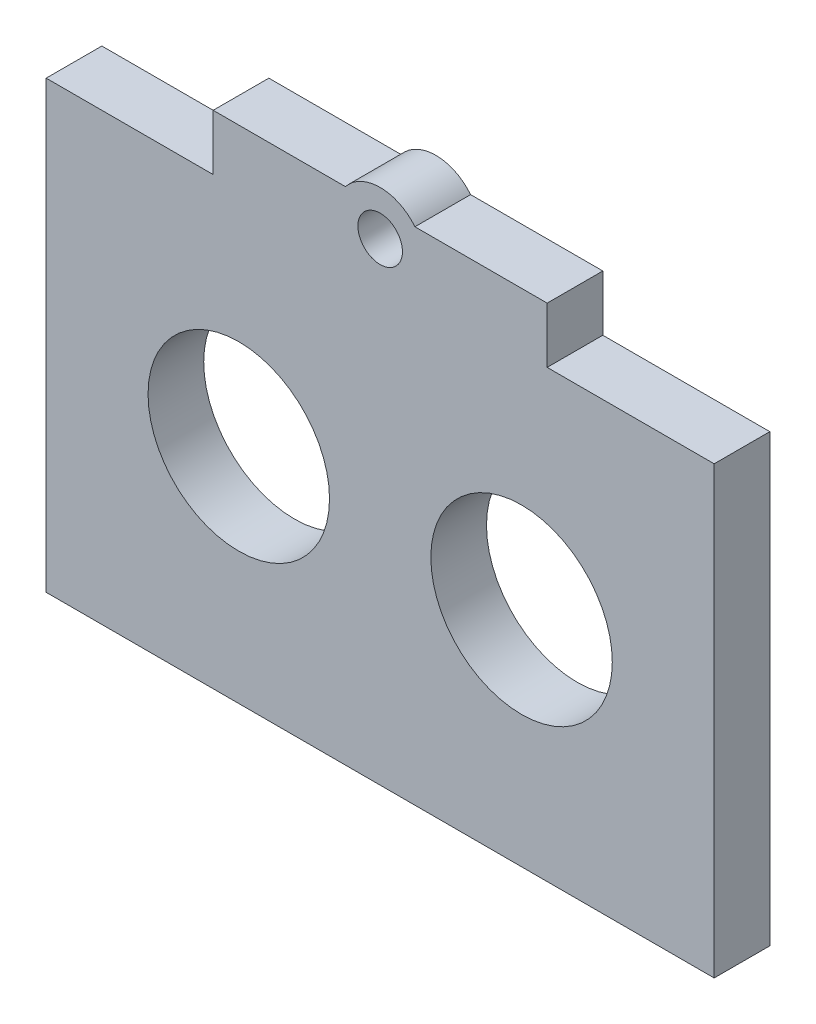
SolidWorks part; units mm, degrees
ref_plane "Plan de face" through (0, 0, 0) normal (0, 0, 1) x (1, 0, 0)
ref_plane "Plan de dessus" through (0, 0, 0) normal (0, 1, 0) x (1, 0, 0)
ref_plane "Plan de droite" through (0, 0, 0) normal (1, 0, 0) x (0, 0, -1)
sketch "Esquisse1" plane through (0, 0, 0) normal (0, 0, 1) x (1, 0, 0)
  line L1 (-30, -20) -> (30, -20)
  line L2 (-30, -20) -> (-30, 20)
  line L3 (-30, 20) -> (30, 20)
  line L4 (30, -20) -> (30, 20)
  line L5 (0, 20) -> (0, -20) construction
  line L6 (-30, 0) -> (30, 0) construction
  line L7 (15, 15) -> (-15, 15)
  line L8 (15, 15) -> (15, 25)
  line L9 (15, 25) -> (-15, 25)
  line L10 (-15, 15) -> (-15, 25)
  line L11 (0, 25) -> (0, 15) construction
  line L12 (15, 20) -> (-15, 20) construction
  circle A0 centre (-12.7, 0) radius 8.15
  circle A1 centre (12.7, 0) radius 8.15
  circle A2 centre (0, 22.5) radius 2
  circle A4 centre (0, 22.5) radius 4
  point P0 (0, 0)
  dimension "D3" = 25.4
  dimension "D5" = 5
  dimension "D8" = 4
  dimension "D10" = 16.3
  dimension "D9" = 16.3
  dimension "D1" = 60
  dimension "D2" = 40
  dimension "D4" = 12.7
  dimension "D6" = 30
  dimension "D7" = 2.5
extrude "Boss.-Extru.1" add sketch "Esquisse1" along normal blind 5 contours L7 L10 L3 L2 L1 L4 L8 A1 A0 | A4 L3 L10 L7 L8 | A4 L9 L10 L3 | A4 L3 L8 L9 | L3 A4 | L9 A4 L3 A2 | L9 A4
